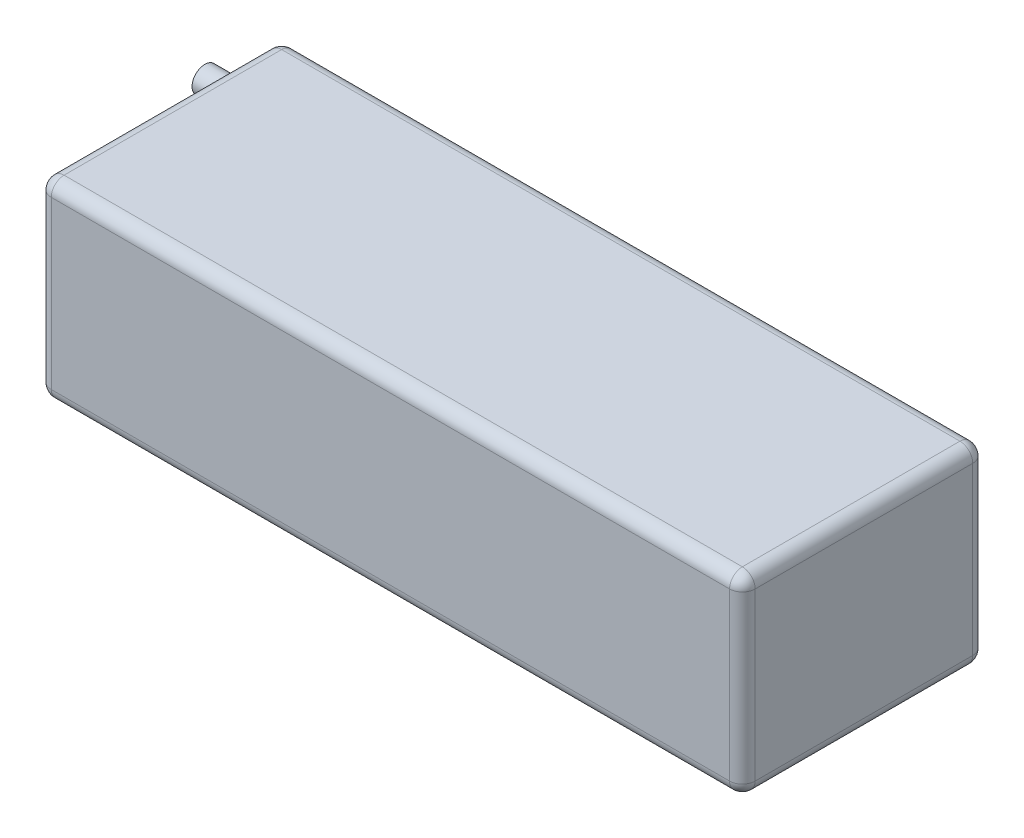
SolidWorks part; units mm, degrees
ref_plane "Front Plane" through (0, 0, 0) normal (0, 0, 1) x (1, 0, 0)
ref_plane "Top Plane" through (0, 0, 0) normal (0, 1, 0) x (1, 0, 0)
ref_plane "Right Plane" through (0, 0, 0) normal (1, 0, 0) x (0, 0, -1)
sketch "Sketch1" plane through (0, 0, 0) normal (0, 1, 0) x (1, 0, 0)
  line L1 (55, -19) -> (-55, -19)
  line L2 (55, -19) -> (55, 19)
  line L3 (55, 19) -> (-55, 19)
  line L4 (-55, -19) -> (-55, 19)
  line L5 (55, -19) -> (-55, 19) construction
  line L6 (55, 19) -> (-55, -19) construction
  point P0 (0, 0)
  dimension "D1" = 110
  dimension "D2" = 38
extrude "Boss-Extrude1" add sketch "Sketch1" along normal blind 30
fillet "Fillet1" radius 2 12 edges at (-55, 15, -19) (0, 30, -19) (-55, 30, 0) (-55, 15, 19) (0, 30, 19) (55, 15, 19) (55, 30, 0) (55, 15, -19) (0, 0, 19) (55, 0, 0) (0, 0, -19) (-55, 0, 0)
sketch "Sketch2" plane through (-55, 0, 0) normal (-1, 0, 0) x (0, 0, 1)
  line L0 (-17, 28) -> (-17, 2) construction
  line L1 (-17, 20) -> (-17, 15) construction
  line L2 (-17, 15) -> (-17, 10) construction
  circle A0 centre (-17, 20) radius 2
  circle A1 centre (-17, 15) radius 2
  circle A2 centre (-17, 10) radius 2
  dimension "D1" = 4
  dimension "D2" = 5
extrude "Boss-Extrude2" add sketch "Sketch2" along normal mid plane 20
